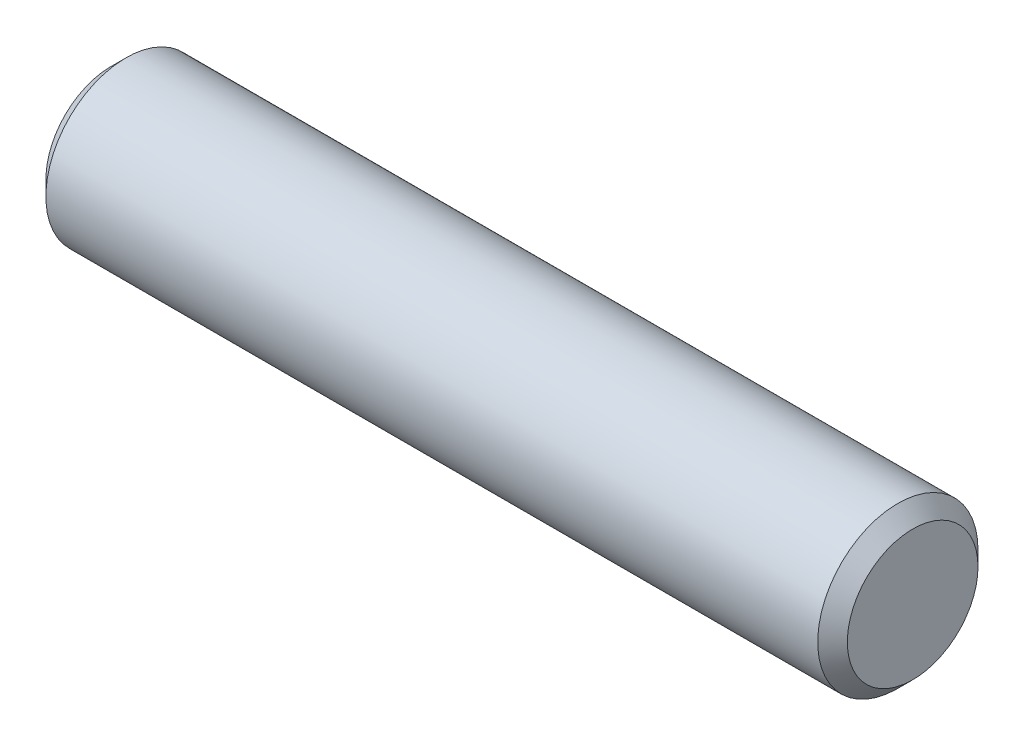
SolidWorks part; units mm, degrees
revolve "BaseBody" add sketch "BodySke" angle 360 about L14
sketch "BodySke" plane through (0, 0, 0) normal (0, 0, 1) x (1, 0, 0)
  line L0 (25.109, 15.875) -> (25.109, -6.35) construction
  line L1 (1, 15.875) -> (1, -3.175) construction
  line L2 (30, 6.35) -> (30, 3.175) construction
  line L10 (0, 3) -> (30, 3)
  line L12 (30, 3) -> (30, 0)
  line L13 (30, 0) -> (0, 0)
  line L14 (-3.175, 0) -> (107.95, 0) construction
  line L18 (0, 3) -> (0, 0)
  dimension "Diameter" = 6
  dimension "Length" = 30
  dimension "Advance" = 1
  dimension "Minor_dia" = 4.891
  dimension "Thread_max" = 30
cosmetic thread "ThreadCosmetic" parameters "Thread_minor"=4.891
ref_plane "Plane1" through (0, 0, 0) normal (0, 0, 1) x (1, 0, 0)
ref_plane "Plane2" through (0, 0, 0) normal (0, 1, 0) x (1, 0, 0)
ref_plane "Plane3" through (0, 0, 0) normal (1, 0, 0) x (0, 0, -1)
chamfer "Chamfer1" distance 0.5545 angle 45 2 edges at (30, 0, 3) (0, 0, 3)
sketch "ThdSchSke" plane through (0, 0, 0) normal (0, 0, 1) x (1, 0, 0)
  line L0 (0.3883, -2.4455) -> (0, -3)
  line L1 (0.3883, -2.4455) -> (0.7765, -3)
  line L2 (0.7765, -3) -> (0.7765, -3.75)
  line L3 (-3.175, 0) -> (5.1513, 0) construction
  line L4 (0, 3) -> (0, -3) construction
  line L5 (0.7765, -3.75) -> (0, -3.75)
  line L6 (0, -3.75) -> (0, -3)
  dimension "Thread_minor" = 4.891
  dimension "Diameter" = 6
revolve "ThreadSchematic" [suppressed] cut sketch "ThdSchSke" angle 360 about L3
pattern_linear "ThdSchPat" [suppressed]
equation "\"Thread_minor@ThreadCosmetic\" = \"Minor_dia@BodySke\""
equation "\"Chamfer@Chamfer1\" =  ( \"Diameter@BodySke\" - \"Minor_dia@BodySke\" ) / 2"
equation "\"Thread_minor@ThdSchSke\" = \"Minor_dia@BodySke\""
equation "\"Diameter@ThdSchSke\" = \"Diameter@BodySke\""
equation "\"Overcut@ThdSchSke\" = \"Diameter@BodySke\" * 1.25"
equation "\"Num_threads@ThdSchPat\" = int( (\"Thread_max@BodySke\" - \"Advance@BodySke\" ) / \"Advance@BodySke\" + 0.999 ) + 1"
equation "\"Advance@ThdSchPat\" = \"Thread_max@BodySke\" /  ( \"Num_threads@ThdSchPat\" - 1 ) 'relax it"
equation "\"Num_threads@ThdSchPat\" = \"Num_threads@ThdSchPat\" - sgn( \"Num_threads@ThdSchPat\" - 1 ) '---chamfered tips only---"
